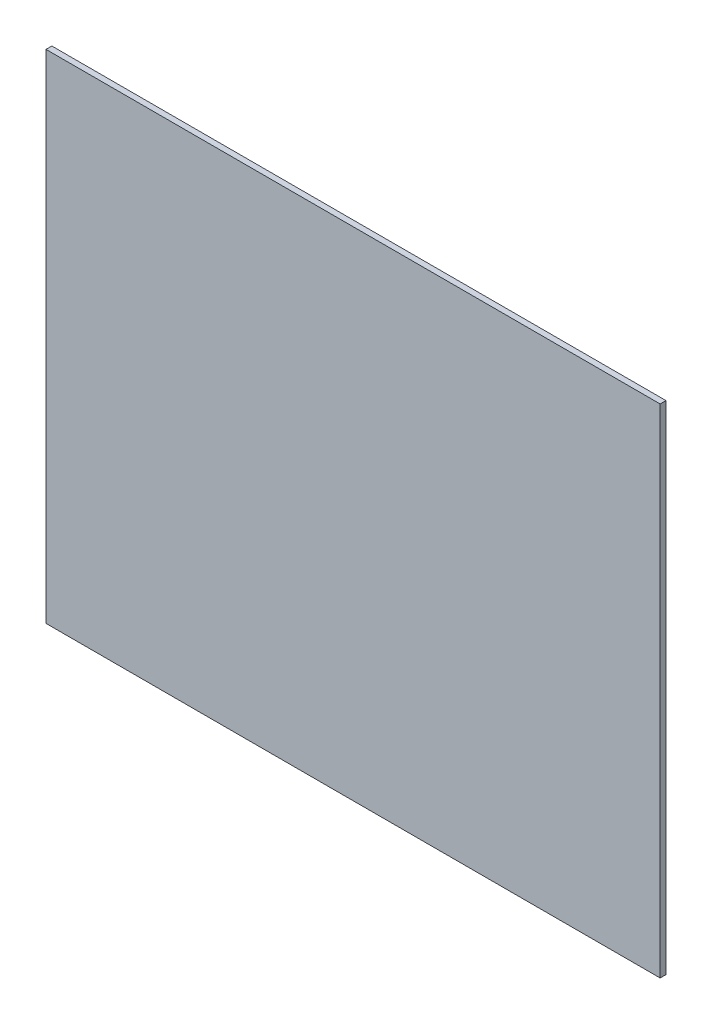
SolidWorks part; units mm, degrees
material "3003 Alloy"
ref_plane "Front Plane" through (0, 0, 0) normal (0, 0, 1) x (1, 0, 0)
ref_plane "Top Plane" through (0, 0, 0) normal (0, 1, 0) x (1, 0, 0)
ref_plane "Right Plane" through (0, 0, 0) normal (1, 0, 0) x (0, 0, -1)
sketch "Sketch1" plane through (0, 0, 0) normal (0, 0, 1) x (1, 0, 0)
  line L1 (105, -85) -> (-105, -85)
  line L2 (105, -85) -> (105, 85)
  line L3 (105, 85) -> (-105, 85)
  line L4 (-105, -85) -> (-105, 85)
  line L5 (105, -85) -> (-105, 85) construction
  line L6 (105, 85) -> (-105, -85) construction
  point P0 (0, 0)
  dimension "D1" = 210
  dimension "D2" = 170
extrude "Boss-Extrude1" add sketch "Sketch1" along normal blind 2
